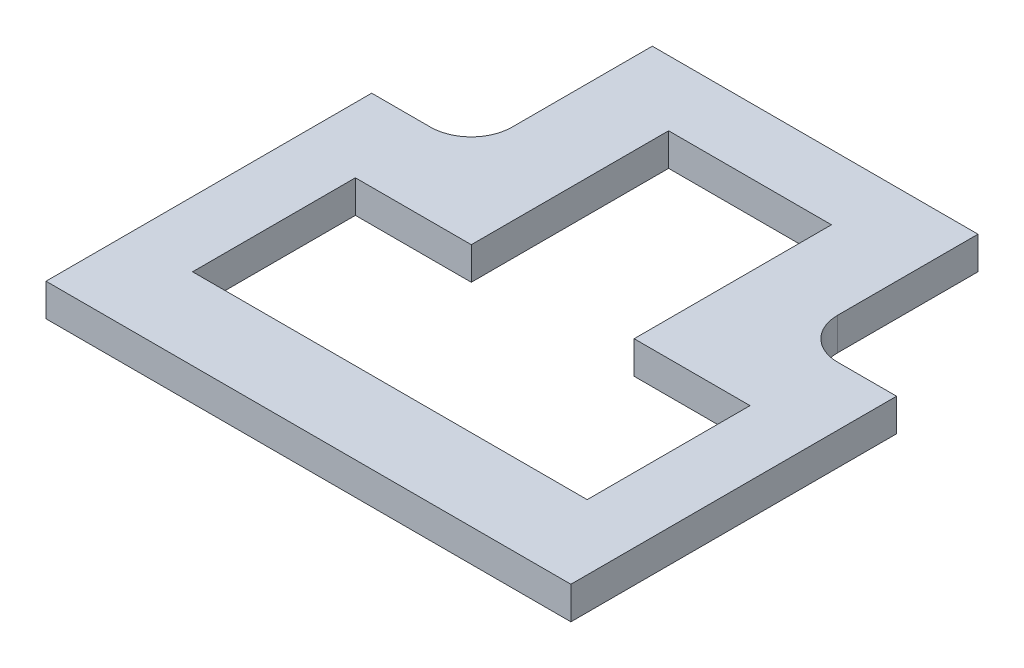
SolidWorks part; units mm, degrees
ref_plane "Alzado" through (0, 0, 0) normal (0, 0, 1) x (1, 0, 0)
ref_plane "Planta" through (0, 0, 0) normal (0, 1, 0) x (1, 0, 0)
ref_plane "Vista lateral" through (0, 0, 0) normal (1, 0, 0) x (0, 0, -1)
sketch "Croquis1" plane through (0, 0, 0) normal (0, 1, 0) x (1, 0, 0)
  line L1 (-15, 15) -> (15, 15)
  line L2 (-15, 15) -> (-15, -15)
  line L3 (-15, -15) -> (15, -15)
  line L4 (15, 15) -> (15, -15)
  line L5 (-15, 15) -> (15, -15) construction
  line L6 (-15, -15) -> (15, 15) construction
  point P0 (0, 0)
extrude "Saliente-Extruir1" add sketch "Croquis1" along normal blind 3
sketch "Croquis2" plane through (0, 3, 0) normal (0, 1, 0) x (1, 0, 0)
  line L1 (-15, -15) -> (-30, -15)
  line L2 (-15, -15) -> (-15, -45)
  line L3 (-15, -45) -> (-30, -45)
  line L4 (-30, -15) -> (-30, -45)
  line L5 (15, -15) -> (30, -15)
  line L6 (15, -15) -> (15, -45)
  line L7 (15, -45) -> (30, -45)
  line L8 (30, -15) -> (30, -45)
extrude "Saliente-Extruir3" add sketch "Croquis2" against normal blind 3 separate body
sketch "Croquis3" plane through (0, 3, 0) normal (0, 1, 0) x (1, 0, 0)
  line L1 (-15, -15) -> (15, -15)
  line L2 (-15, -15) -> (-15, -45)
  line L3 (-15, -45) -> (15, -45)
  line L4 (15, -15) -> (15, -45)
extrude "Saliente-Extruir4" add sketch "Croquis3" against normal blind 3
sketch "Croquis4" plane through (0, 3, 0) normal (0, 1, 0) x (1, 0, 0)
  line L0 (-30, 0) -> (-45, 0)
  line L1 (-30, -15) -> (-30, -45) construction
  line L2 (-15, 15) -> (-15, -15) construction
  line L3 (-15, -15) -> (-30, -15) construction
  line L4 (-45, 0) -> (-45, -60)
  line L5 (-45, -60) -> (45, -60)
  line L6 (45, -60) -> (45, 0)
  line L7 (45, 0) -> (30, 0)
  line L8 (30, 0) -> (30, 30)
  line L9 (30, 30) -> (-30, 30)
  line L10 (-30, 30) -> (-30, 0)
  dimension "D1" = 15
  dimension "D2" = 15
  dimension "D3" = 15
extrude "Saliente-Extruir5" add sketch "Croquis4" along normal blind 3
sketch "Croquis5" plane through (0, 0, 0) normal (0, -1, 0) x (-1, 0, 0)
  line L0 (30, -45) -> (30, -15)
  line L1 (30, -15) -> (15, -15)
  line L2 (15, -15) -> (15, 15)
  line L3 (15, 15) -> (-15, 15)
  line L4 (-15, 15) -> (-15, -15)
  line L5 (-15, -15) -> (-30, -15)
  line L6 (-30, -15) -> (-30, -45)
  line L7 (-30, -45) -> (30, -45)
extrude "Cortar-Extruir1" cut sketch "Croquis5" against normal blind 6
sketch "Croquis6" plane through (0, 3, 0) normal (0, -1, 0) x (-1, 0, 0)
  line L0 (37.5, 0) -> (37.5, 7.5) construction
  line L1 (30, 0) -> (45, 0) construction
  line L2 (37.5, 7.5) -> (30, 7.5) construction
  line L3 (30, 30) -> (30, 0) construction
  line L4 (-37.5, 0) -> (-37.5, 7.5) construction
  line L5 (-45, 0) -> (-30, 0) construction
  line L6 (-37.5, 7.5) -> (-30, 7.5) construction
  line L7 (-30, 0) -> (-30, 30) construction
  line L8 (37.5, 0) -> (45, 0)
  line L9 (45, 0) -> (45, -60)
  line L10 (45, -60) -> (-45, -60)
  line L11 (-45, -60) -> (-45, 0)
  line L12 (-45, 0) -> (-37.5, 0)
  line L13 (-30, 7.5) -> (-30, 30)
  line L14 (-30, 30) -> (30, 30)
  line L15 (30, 30) -> (30, 7.5)
  line L16 (15, 15) -> (15, -15)
  line L17 (15, -15) -> (30, -15)
  line L18 (30, -15) -> (30, -45)
  line L19 (30, -45) -> (-30, -45)
  line L20 (-30, -45) -> (-30, -15)
  line L21 (-30, -15) -> (-15, -15)
  line L22 (-15, -15) -> (-15, 15)
  line L23 (-15, 15) -> (15, 15)
  arc A0 (30, 7.5) -> (37.5, 0) centre (37.5, 7.5) ccw
  arc A1 (-37.5, 0) -> (-30, 7.5) centre (-37.5, 7.5) ccw
extrude "Saliente-Extruir8" add sketch "Croquis6" against normal blind 11 contours L15 L8 L9 L10 L11 L12 L13 L14 L7 L0 L1 L2 L3 L4 L5 L6 | A0 L8 L15 | A1 L11 L10
sketch "Croquis7" plane through (0, 14, 0) normal (0, 1, 0) x (1, 0, 0)
  line L0 (15, -15) -> (15, 15) construction
  line L1 (-15, 15) -> (15, 15)
  line L2 (-15, 15) -> (-15, 18.175)
  line L3 (-15, 18.175) -> (15, 18.175)
  line L4 (15, 15) -> (15, 18.175)
extrude "Cortar-Extruir3" cut sketch "Croquis7" against normal blind 18.542
sketch "Croquis9" plane through (0, 14, 0) normal (0, 1, 0) x (1, 0, 0)
  line L0 (30, 30) -> (30, 7.5) construction
  line L1 (-30, 30) -> (30, 30)
  line L2 (-30, 30) -> (-30, 30.175)
  line L3 (-30, 30.175) -> (30, 30.175)
  line L4 (30, 30) -> (30, 30.175)
  line L5 (15, 18.175) -> (-15, 18.175) construction
  dimension "D1" = 12
extrude "Saliente-Extruir9" add sketch "Croquis9" against normal blind 11
sketch "Croquis10" plane through (0, 0, 60) normal (0, 0, 1) x (1, 0, 0)
  line L0 (45, 14) -> (45, 3) construction
  line L1 (-45, 3) -> (45, 3)
  line L2 (-45, 3) -> (-45, 8)
  line L3 (-45, 8) -> (45, 8)
  line L4 (45, 3) -> (45, 8)
  line L5 (45, 14) -> (-45, 14) construction
  dimension "D1" = 6
extrude "Cortar-Extruir5" cut sketch "Croquis10" against normal blind 93
sketch "Croquis11" plane through (0, 14, 0) normal (0, 1, 0) x (1, 0, 0)
  line L0 (15, -15) -> (15, 18.175) construction
  line L1 (-15, 18.175) -> (15, 18.175)
  line L2 (-15, 18.175) -> (-15, 15)
  line L3 (-15, 15) -> (15, 15)
  line L4 (15, 18.175) -> (15, 15)
  line L5 (-15, -15) -> (-30, -15) construction
  dimension "D1" = 30
extrude "Saliente-Extruir10" add sketch "Croquis11" against normal blind 11
sketch "Croquis12" plane through (0, 14, 0) normal (0, 1, 0) x (1, 0, 0)
  line L0 (30, 30.175) -> (30, 7.5) construction
  line L1 (-30, 30.175) -> (30, 30.175)
  line L2 (-30, 30.175) -> (-30, 30)
  line L3 (-30, 30) -> (30, 30)
  line L4 (30, 30.175) -> (30, 30)
  line L5 (-15, 15) -> (15, 15) construction
  dimension "D1" = 15
extrude "Cortar-Extruir6" cut sketch "Croquis12" against normal blind 11
sketch "Croquis14" plane through (0, 14, 0) normal (0, 1, 0) x (1, 0, 0)
  line L0 (15, -15) -> (15, 15) construction
  line L1 (-15, 15) -> (15, 15)
  line L2 (-15, 15) -> (-15, 21.35)
  line L3 (-15, 21.35) -> (15, 21.35)
  line L4 (15, 15) -> (15, 21.35)
extrude "Cortar-Extruir8" cut sketch "Croquis14" against normal blind 19.812
sketch "Croquis15" plane through (0, 14, 0) normal (0, 1, 0) x (1, 0, 0)
  line L0 (-30, 7.5) -> (-30, 30) construction
  line L1 (-30, 27.0346) -> (30, 27.0346)
  line L2 (-30, 27.0346) -> (-30, 33.35)
  line L3 (-30, 33.35) -> (30, 33.35)
  line L4 (30, 27.0346) -> (30, 33.35)
  line L5 (30, 30) -> (30, 7.5) construction
  line L6 (15, 21.35) -> (-15, 21.35) construction
  dimension "D1" = 12
extrude "Saliente-Extruir14" add sketch "Croquis15" against normal blind 6
sketch "Croquis16" plane through (0, 14, 0) normal (0, 1, 0) x (1, 0, 0)
  line L1 (-30, -15) -> (-36.35, -15)
  line L2 (-30, -15) -> (-30, -45)
  line L3 (-30, -45) -> (-36.35, -45)
  line L4 (-36.35, -15) -> (-36.35, -45)
  line L5 (30, -15) -> (36.35, -15)
  line L6 (30, -15) -> (30, -45)
  line L7 (30, -45) -> (36.35, -45)
  line L8 (36.35, -15) -> (36.35, -45)
extrude "Cortar-Extruir9" cut sketch "Croquis16" against normal blind 10
sketch "Croquis17" plane through (0, 14, 0) normal (0, 1, 0) x (1, 0, 0)
  line L0 (-36.35, -15) -> (-36.35, -45) construction
  line L1 (-45, 0) -> (-48.35, 0)
  line L2 (-45, 0) -> (-45, -60)
  line L3 (-45, -60) -> (-48.35, -60)
  line L4 (-48.35, 0) -> (-48.35, -60)
  line L5 (36.35, -45) -> (36.35, -15) construction
  line L6 (45, 0) -> (48.35, 0)
  line L7 (45, 0) -> (45, -60)
  line L8 (45, -60) -> (48.35, -60)
  line L9 (48.35, 0) -> (48.35, -60)
  dimension "D1" = 12
  dimension "D2" = 12
extrude "Saliente-Extruir15" add sketch "Croquis17" against normal blind 6
